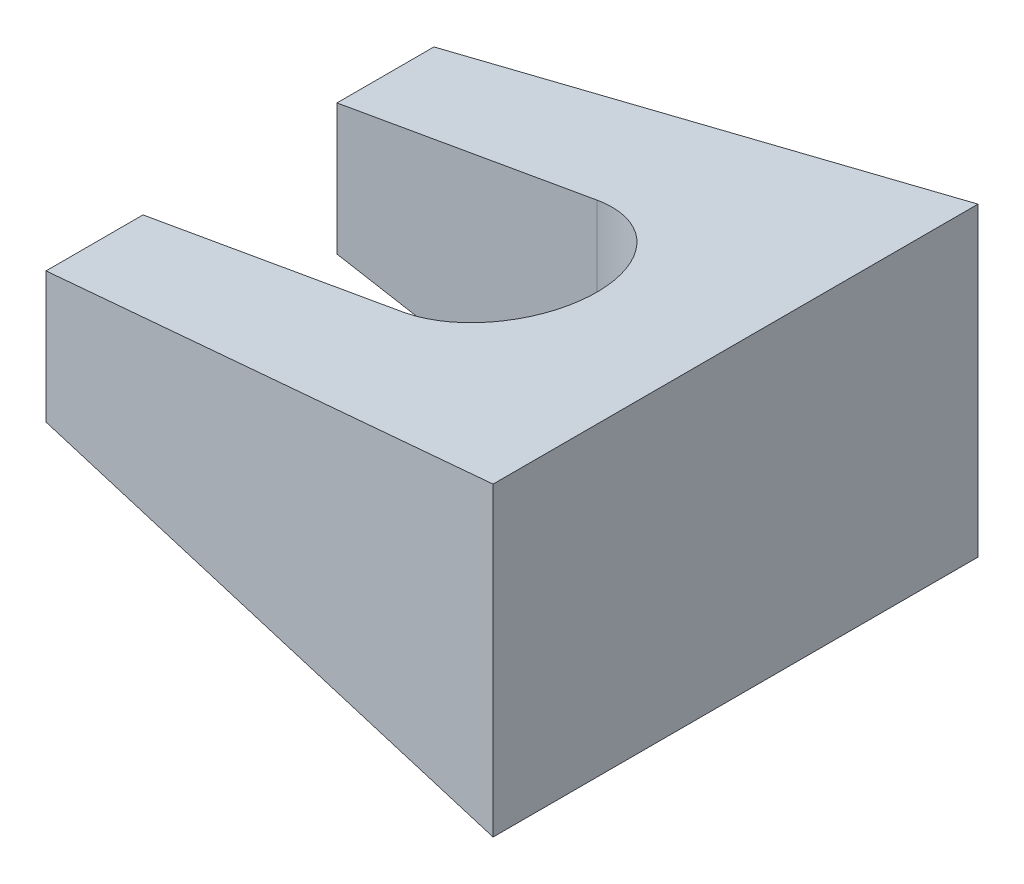
SolidWorks part; units mm, degrees
ref_plane "Front Plane" through (0, 0, 0) normal (0, 0, 1) x (1, 0, 0)
ref_plane "Top Plane" through (0, 0, 0) normal (0, 1, 0) x (1, 0, 0)
ref_plane "Right Plane" through (0, 0, 0) normal (1, 0, 0) x (0, 0, -1)
sketch "Sketch1" plane through (0, 0, 0) normal (0, 1, 0) x (1, 0, 0)
  line L0 (-20.7742, 0) -> (33.5484, 0) construction
  line L1 (-12.774, -10) -> (-12.774, 10)
  line L2 (-12.774, 10) -> (12.774, 12.5)
  line L3 (12.774, 12.5) -> (12.774, -12.5)
  line L4 (-12.774, -10) -> (12.774, -12.5)
  point P5 (0, 11.25)
  point P9 (12.774, 0)
  point P10 (-12.774, 0)
  dimension "D1" = 20
  dimension "D2" = 25
  dimension "D3" = 25.67
extrude "Boss-Extrude1" add sketch "Sketch1" along normal mid plane 50
sketch "Sketch2" plane through (0, 0, 0) normal (0, 0, 1) x (1, 0, 0)
  line L10 (-12.774, -3.3753) -> (-12.774, 3.3753)
  line L11 (-12.774, 25) -> (-12.774, -25) construction
  line L18 (-12.774, 3.3753) -> (12.774, 7.8801)
  line L19 (12.774, 25) -> (12.774, -25) construction
  line L20 (12.774, 7.8801) -> (12.774, -7.8801)
  line L21 (-23.624, 0) -> (21.984, 0) construction
  line L22 (-12.774, -3.3753) -> (12.774, -7.8801)
  line L23 (-12.4961, 3.4243) -> (-12.774, 5) construction
  point P11 (12.774, 0)
  point P12 (-12.774, 0)
  dimension "D1" = 5
  dimension "D2" = 10
  dimension "D3" = 1.6
extrude "Cut-Extrude1" cut sketch "Sketch2" against normal through all both and the other way through all flip side to cut
sketch "Sketch3" plane through (0, 0, 0) normal (0, 1, 0) x (1, 0, 0)
  line L0 (-17.8169, 5) -> (0.6203, 5)
  line L1 (-19.1954, 0) -> (15.7147, 0) construction
  line L2 (-17.8169, -5) -> (0.6203, -5)
  line L3 (-17.8169, 5) -> (-17.8169, -5)
  arc A0 (0.6203, 5) -> (0.6203, -5) centre (0.6203, 0) cw
  dimension "D1" = 10
extrude "Cut-Extrude2" cut sketch "Sketch3" against normal through all both and the other way through all
